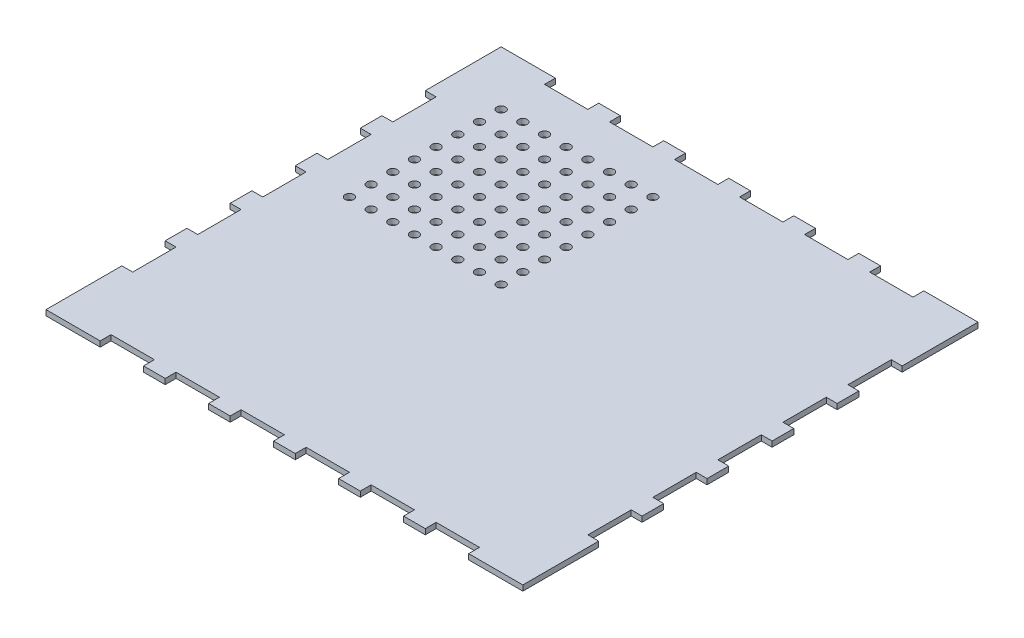
SolidWorks part; units mm, degrees
ref_plane "Front Plane" through (0, 0, 0) normal (0, 0, 1) x (1, 0, 0)
ref_plane "Top Plane" through (0, 0, 0) normal (0, 1, 0) x (1, 0, 0)
ref_plane "Right Plane" through (0, 0, 0) normal (1, 0, 0) x (0, 0, -1)
sketch "Sketch7" plane through (0, 0, 0) normal (0, 1, 0) x (1, 0, 0)
  line L0 (-133.35, 127) -> (133.35, -127) construction
  line L1 (133.35, 127) -> (-133.35, 127)
  line L2 (133.35, 127) -> (133.35, -127)
  line L3 (133.35, -127) -> (-133.35, -127)
  line L4 (-133.35, 127) -> (-133.35, -127)
  circle A0 centre (-107.95, 101.6) radius 2.54
  circle A1 centre (-95.25, 101.6) radius 2.54
  circle A2 centre (-82.55, 101.6) radius 2.54
  circle A3 centre (-69.85, 101.6) radius 2.54
  circle A4 centre (-57.15, 101.6) radius 2.54
  circle A5 centre (-44.45, 101.6) radius 2.54
  circle A6 centre (-31.75, 101.6) radius 2.54
  circle A7 centre (-19.05, 101.6) radius 2.54
  circle A18 centre (-95.25, 88.9) radius 2.54
  circle A19 centre (-82.55, 88.9) radius 2.54
  circle A20 centre (-69.85, 88.9) radius 2.54
  circle A21 centre (-57.15, 88.9) radius 2.54
  circle A22 centre (-44.45, 88.9) radius 2.54
  circle A23 centre (-31.75, 88.9) radius 2.54
  circle A24 centre (-19.05, 88.9) radius 2.54
  circle A35 centre (-95.25, 76.2) radius 2.54
  circle A36 centre (-82.55, 76.2) radius 2.54
  circle A37 centre (-69.85, 76.2) radius 2.54
  circle A38 centre (-57.15, 76.2) radius 2.54
  circle A39 centre (-44.45, 76.2) radius 2.54
  circle A40 centre (-31.75, 76.2) radius 2.54
  circle A41 centre (-19.05, 76.2) radius 2.54
  circle A52 centre (-95.25, 63.5) radius 2.54
  circle A53 centre (-82.55, 63.5) radius 2.54
  circle A54 centre (-69.85, 63.5) radius 2.54
  circle A55 centre (-57.15, 63.5) radius 2.54
  circle A56 centre (-44.45, 63.5) radius 2.54
  circle A57 centre (-31.75, 63.5) radius 2.54
  circle A58 centre (-19.05, 63.5) radius 2.54
  circle A69 centre (-95.25, 50.8) radius 2.54
  circle A70 centre (-82.55, 50.8) radius 2.54
  circle A71 centre (-69.85, 50.8) radius 2.54
  circle A72 centre (-57.15, 50.8) radius 2.54
  circle A73 centre (-44.45, 50.8) radius 2.54
  circle A74 centre (-31.75, 50.8) radius 2.54
  circle A75 centre (-19.05, 50.8) radius 2.54
  circle A86 centre (-95.25, 38.1) radius 2.54
  circle A87 centre (-82.55, 38.1) radius 2.54
  circle A88 centre (-69.85, 38.1) radius 2.54
  circle A89 centre (-57.15, 38.1) radius 2.54
  circle A90 centre (-44.45, 38.1) radius 2.54
  circle A91 centre (-31.75, 38.1) radius 2.54
  circle A92 centre (-19.05, 38.1) radius 2.54
  circle A103 centre (-95.25, 25.4) radius 2.54
  circle A104 centre (-82.55, 25.4) radius 2.54
  circle A105 centre (-69.85, 25.4) radius 2.54
  circle A106 centre (-57.15, 25.4) radius 2.54
  circle A107 centre (-44.45, 25.4) radius 2.54
  circle A108 centre (-31.75, 25.4) radius 2.54
  circle A109 centre (-19.05, 25.4) radius 2.54
  circle A120 centre (-95.25, 12.7) radius 2.54
  circle A121 centre (-82.55, 12.7) radius 2.54
  circle A122 centre (-69.85, 12.7) radius 2.54
  circle A123 centre (-57.15, 12.7) radius 2.54
  circle A124 centre (-44.45, 12.7) radius 2.54
  circle A125 centre (-31.75, 12.7) radius 2.54
  circle A126 centre (-19.05, 12.7) radius 2.54
  circle A290 centre (-107.95, 88.9) radius 2.54
  circle A291 centre (-107.95, 76.2) radius 2.54
  circle A292 centre (-107.95, 63.5) radius 2.54
  circle A293 centre (-107.95, 50.8) radius 2.54
  circle A294 centre (-107.95, 38.1) radius 2.54
  circle A295 centre (-107.95, 25.4) radius 2.54
  circle A296 centre (-107.95, 12.7) radius 2.54
  point P5 (0, 0)
  point P6 (-49.022, -30.226)
  point P7 (49.022, -30.226)
  point P8 (49.022, 67.818)
  point P9 (0, 0)
  dimension "D1" = 5.08
  dimension "D2" = 25.4
  dimension "D3" = 254
  dimension "D6" = 8
  dimension "D9" = 266.7
  dimension "D4" = 25.4
  dimension "D5" = 8
extrude "Boss-Extrude4" add sketch "Sketch7" along normal blind 3.175
sketch "Sketch8" plane through (0, 0, 0) normal (0, 1, 0) x (1, 0, 0)
  line L0 (-120.65, 127) -> (-120.65, 133.35)
  line L1 (-120.65, 133.35) -> (-107.95, 133.35)
  line L2 (-107.95, 133.35) -> (-107.95, 127)
  line L3 (133.35, 127) -> (-133.35, 127) construction
  line L4 (-120.65, 127) -> (-107.95, 127)
  line L5 (-82.55, 127) -> (-82.55, 133.35)
  line L6 (-82.55, 133.35) -> (-69.85, 133.35)
  line L7 (-69.85, 133.35) -> (-69.85, 127)
  line L8 (-82.55, 127) -> (-69.85, 127)
  line L9 (-44.45, 127) -> (-44.45, 133.35)
  line L10 (-44.45, 133.35) -> (-31.75, 133.35)
  line L11 (-31.75, 133.35) -> (-31.75, 127)
  line L12 (-44.45, 127) -> (-31.75, 127)
  line L13 (-6.35, 127) -> (-6.35, 133.35)
  line L14 (-6.35, 133.35) -> (6.35, 133.35)
  line L15 (6.35, 133.35) -> (6.35, 127)
  line L16 (-6.35, 127) -> (6.35, 127)
  line L17 (31.75, 127) -> (31.75, 133.35)
  line L18 (31.75, 133.35) -> (44.45, 133.35)
  line L19 (44.45, 133.35) -> (44.45, 127)
  line L20 (31.75, 127) -> (44.45, 127)
  line L21 (69.85, 127) -> (69.85, 133.35)
  line L22 (69.85, 133.35) -> (82.55, 133.35)
  line L23 (82.55, 133.35) -> (82.55, 127)
  line L24 (69.85, 127) -> (82.55, 127)
  line L25 (107.95, 127) -> (107.95, 133.35)
  line L26 (107.95, 133.35) -> (120.65, 133.35)
  line L27 (120.65, 133.35) -> (120.65, 127)
  line L28 (107.95, 127) -> (120.65, 127)
  line L29 (133.35, -127) -> (133.35, 127) construction
  line L30 (-120.65, -133.35) -> (-120.65, -127)
  line L31 (-120.65, -127) -> (-107.95, -127)
  line L32 (-107.95, -127) -> (-107.95, -133.35)
  line L33 (-120.65, -133.35) -> (-107.95, -133.35)
  line L34 (-82.55, -133.35) -> (-82.55, -127)
  line L35 (-82.55, -127) -> (-69.85, -127)
  line L36 (-69.85, -127) -> (-69.85, -133.35)
  line L37 (-82.55, -133.35) -> (-69.85, -133.35)
  line L38 (-44.45, -133.35) -> (-44.45, -127)
  line L39 (-44.45, -127) -> (-31.75, -127)
  line L40 (-31.75, -127) -> (-31.75, -133.35)
  line L41 (-44.45, -133.35) -> (-31.75, -133.35)
  line L42 (-6.35, -133.35) -> (-6.35, -127)
  line L43 (-6.35, -127) -> (6.35, -127)
  line L44 (6.35, -127) -> (6.35, -133.35)
  line L45 (-6.35, -133.35) -> (6.35, -133.35)
  line L46 (31.75, -133.35) -> (31.75, -127)
  line L47 (31.75, -127) -> (44.45, -127)
  line L48 (44.45, -127) -> (44.45, -133.35)
  line L49 (31.75, -133.35) -> (44.45, -133.35)
  line L50 (69.85, -133.35) -> (69.85, -127)
  line L51 (69.85, -127) -> (82.55, -127)
  line L52 (82.55, -127) -> (82.55, -133.35)
  line L53 (69.85, -133.35) -> (82.55, -133.35)
  line L54 (107.95, -133.35) -> (107.95, -127)
  line L55 (107.95, -127) -> (120.65, -127)
  line L56 (120.65, -127) -> (120.65, -133.35)
  line L57 (107.95, -133.35) -> (120.65, -133.35)
  line L58 (-133.35, 101.6) -> (-139.7, 101.6)
  line L59 (-133.35, 127) -> (-133.35, -127) construction
  line L60 (-139.7, 101.6) -> (-139.7, 88.9)
  line L61 (-139.7, 88.9) -> (-133.35, 88.9)
  line L62 (-133.35, 101.6) -> (-133.35, 88.9)
  line L63 (-139.7, 50.8) -> (-133.35, 50.8)
  line L64 (-133.35, 63.5) -> (-133.35, 50.8)
  line L65 (-133.35, 63.5) -> (-139.7, 63.5)
  line L66 (-139.7, 63.5) -> (-139.7, 50.8)
  line L67 (-139.7, 12.7) -> (-133.35, 12.7)
  line L68 (-133.35, 25.4) -> (-133.35, 12.7)
  line L69 (-133.35, 25.4) -> (-139.7, 25.4)
  line L70 (-139.7, 25.4) -> (-139.7, 12.7)
  line L71 (-139.7, -25.4) -> (-133.35, -25.4)
  line L72 (-133.35, -12.7) -> (-133.35, -25.4)
  line L73 (-133.35, -12.7) -> (-139.7, -12.7)
  line L74 (-139.7, -12.7) -> (-139.7, -25.4)
  line L75 (-139.7, -63.5) -> (-133.35, -63.5)
  line L76 (-133.35, -50.8) -> (-133.35, -63.5)
  line L77 (-133.35, -50.8) -> (-139.7, -50.8)
  line L78 (-139.7, -50.8) -> (-139.7, -63.5)
  line L79 (-139.7, -101.6) -> (-133.35, -101.6)
  line L80 (-133.35, -88.9) -> (-133.35, -101.6)
  line L81 (-133.35, -88.9) -> (-139.7, -88.9)
  line L82 (-139.7, -88.9) -> (-139.7, -101.6)
  line L96 (139.7, 101.6) -> (133.35, 101.6)
  line L97 (133.35, 101.6) -> (133.35, 88.9)
  line L98 (133.35, 88.9) -> (139.7, 88.9)
  line L99 (139.7, 101.6) -> (139.7, 88.9)
  line L100 (133.35, 50.8) -> (139.7, 50.8)
  line L101 (139.7, 63.5) -> (139.7, 50.8)
  line L102 (139.7, 63.5) -> (133.35, 63.5)
  line L103 (133.35, 63.5) -> (133.35, 50.8)
  line L104 (133.35, 12.7) -> (139.7, 12.7)
  line L105 (139.7, 25.4) -> (139.7, 12.7)
  line L106 (139.7, 25.4) -> (133.35, 25.4)
  line L107 (133.35, 25.4) -> (133.35, 12.7)
  line L108 (133.35, -25.4) -> (139.7, -25.4)
  line L109 (139.7, -12.7) -> (139.7, -25.4)
  line L110 (139.7, -12.7) -> (133.35, -12.7)
  line L111 (133.35, -12.7) -> (133.35, -25.4)
  line L112 (133.35, -63.5) -> (139.7, -63.5)
  line L113 (139.7, -50.8) -> (139.7, -63.5)
  line L114 (139.7, -50.8) -> (133.35, -50.8)
  line L115 (133.35, -50.8) -> (133.35, -63.5)
  line L116 (133.35, -101.6) -> (139.7, -101.6)
  line L117 (139.7, -88.9) -> (139.7, -101.6)
  line L118 (139.7, -88.9) -> (133.35, -88.9)
  line L119 (133.35, -88.9) -> (133.35, -101.6)
  line L132 (-139.7, -139.7) -> (-133.35, -139.7) [skipped]
  line L133 (-133.35, -127) -> (-133.35, -139.7) [skipped]
  line L134 (-133.35, -127) -> (-139.7, -127) [skipped]
  line L135 (-139.7, -127) -> (-139.7, -139.7) [skipped]
  line L136 (-139.7, -177.8) -> (-133.35, -177.8) [skipped]
  line L137 (-133.35, -165.1) -> (-133.35, -177.8) [skipped]
  line L138 (-133.35, -165.1) -> (-139.7, -165.1) [skipped]
  line L139 (-139.7, -165.1) -> (-139.7, -177.8) [skipped]
  line L140 (-133.35, -203.2) -> (-133.35, -215.9) [skipped]
  line L141 (-133.35, -203.2) -> (-139.7, -203.2) [skipped]
  line L142 (-139.7, -203.2) -> (-139.7, -215.9) [skipped]
  line L143 (-139.7, -215.9) -> (-133.35, -215.9) [skipped]
  dimension "D1" = 12.7
  dimension "D2" = 6.35
  dimension "D3" = 12.7
  dimension "D4" = 7
  dimension "D5" = 25.4
  dimension "D6" = 12.7
  dimension "D8" = 25.4
  dimension "D10" = 127
  dimension "D11" = 127
  dimension "D13" = 25.4
  dimension "D7" = 2
  dimension "D9" = 9
extrude "Boss-Extrude5" add sketch "Sketch8" along normal blind 3.175
sketch "Sketch9" plane through (0, 0, 0) normal (0, 1, 0) x (1, 0, 0)
  line L0 (-139.7, 101.6) -> (-139.7, 133.35)
  line L1 (-139.7, 133.35) -> (-120.65, 133.35)
  line L2 (-120.65, 133.35) -> (-120.65, 101.6)
  line L3 (-120.65, 101.6) -> (-139.7, 101.6)
  line L4 (120.65, 133.35) -> (139.7, 133.35)
  line L5 (139.7, 133.35) -> (139.7, 101.6)
  line L6 (139.7, 101.6) -> (120.65, 101.6)
  line L7 (120.65, 101.6) -> (120.65, 133.35)
  line L8 (139.7, -101.6) -> (139.7, -133.35)
  line L9 (139.7, -133.35) -> (120.65, -133.35)
  line L10 (120.65, -133.35) -> (120.65, -101.6)
  line L11 (120.65, -101.6) -> (139.7, -101.6)
  line L12 (-139.7, -101.6) -> (-139.7, -133.35)
  line L13 (-139.7, -133.35) -> (-120.65, -133.35)
  line L14 (-120.65, -133.35) -> (-107.95, -133.35) construction
  line L15 (-120.65, -133.35) -> (-120.65, -101.6)
  line L16 (-120.65, -101.6) -> (-139.7, -101.6)
extrude "Boss-Extrude6" add sketch "Sketch9" along normal blind 3.175
